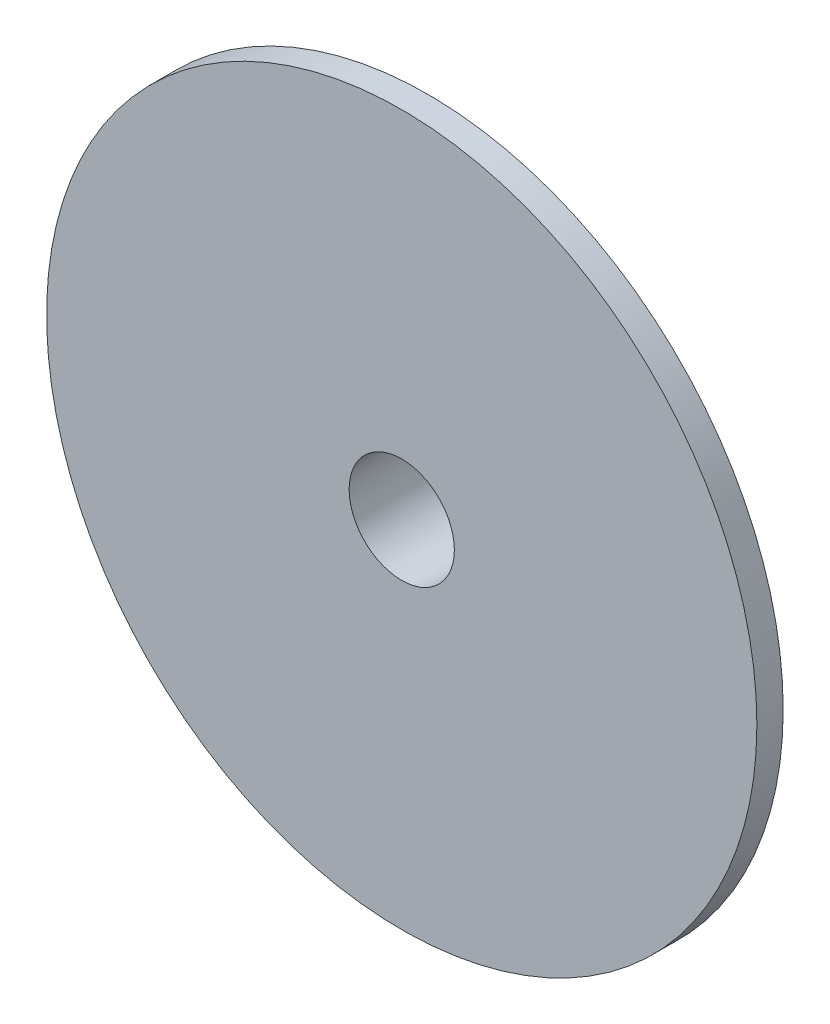
SolidWorks part; units mm, degrees
ref_plane "前视基准面" through (0, 0, 0) normal (0, 0, 1) x (1, 0, 0)
ref_plane "上视基准面" through (0, 0, 0) normal (0, 1, 0) x (1, 0, 0)
ref_plane "右视基准面" through (0, 0, 0) normal (1, 0, 0) x (0, 0, -1)
sketch "草图1" plane through (0, 0, 0) normal (0, 0, 1) x (1, 0, 0)
  circle A0 centre (0, 0) radius 27
extrude "凸台-拉伸1" add sketch "草图1" along normal blind 2
sketch "草图2" plane through (0, 0, 0) normal (0, 0, 1) x (1, 0, 0)
  circle A0 centre (0, 0) radius 5.5
extrude "凸台-拉伸2" add sketch "草图2" against normal blind 15
sketch "草图3" plane through (0, 0, -15) normal (0, 0, -1) x (-1, 0, 0)
  circle A0 centre (0, 0) radius 4
extrude "切除-拉伸1" cut sketch "草图3" against normal blind 150
